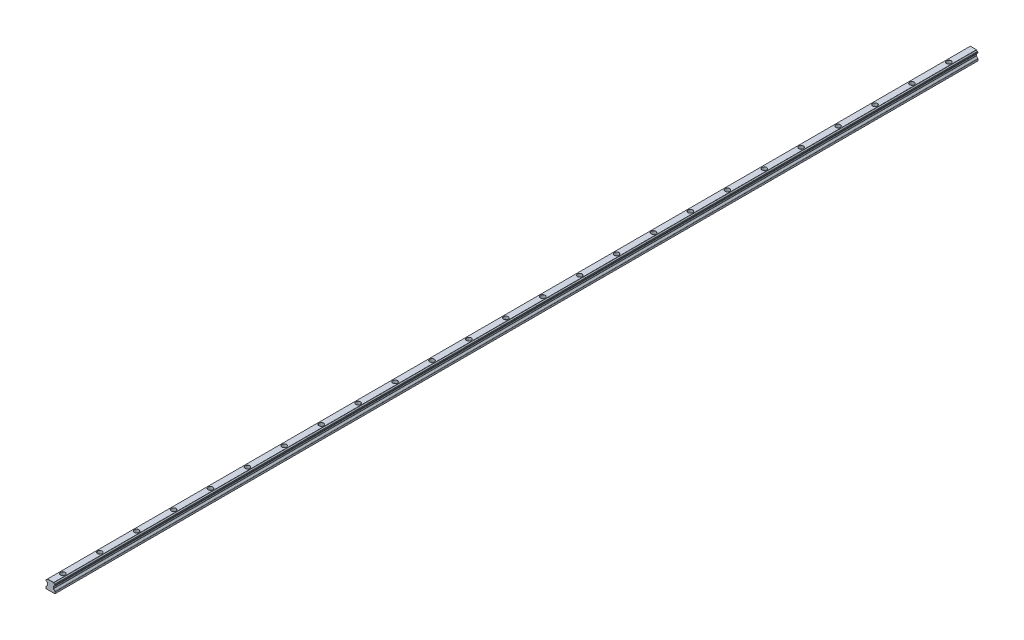
SolidWorks part; units mm, degrees
material "Plain Carbon Steel"
ref_plane "Front Plane" through (0, 0, 0) normal (0, 0, 1) x (1, 0, 0)
ref_plane "Top Plane" through (0, 0, 0) normal (0, 1, 0) x (1, 0, 0)
ref_plane "Right Plane" through (0, 0, 0) normal (1, 0, 0) x (0, 0, -1)
sketch "Rail Profile" plane through (0, 0, 0) normal (0, 0, 1) x (1, 0, 0)
  line L47 (0, 0) -> (0, 20) construction
  line L48 (-7, 0) -> (7, 0)
  line L49 (7, 0) -> (7.5, 0.5)
  line L50 (7.5, 0.5) -> (7.5, 3.0858)
  line L58 (7.2071, 3.7929) -> (4.8672, 6.1328)
  line L59 (4.75, 6.4157) -> (4.75, 8.5843)
  line L60 (4.8672, 8.8672) -> (5.063, 9.063)
  line L61 (7.5, 11.6657) -> (7.5, 12.3343)
  line L62 (-7, 0) -> (-7.5, 0.5)
  line L63 (5, 15) -> (-5, 15)
  line L64 (6.75, 9) -> (6.75, 15) construction
  line L65 (5.063, 14.937) -> (5, 15)
  line L66 (-7.5, 0.5) -> (-7.5, 3.0858)
  line L67 (6.75, 15) -> (3.75, 12) construction
  line L68 (3.75, 12) -> (6.75, 9) construction
  line L69 (7.1, 12.3343) -> (7.1, 11.6657) construction
  line L70 (6.4042, 13.0301) -> (6.4042, 10.9699) construction
  line L71 (-7.2071, 3.7929) -> (-4.8672, 6.1328)
  line L72 (-4.75, 6.4157) -> (-4.75, 8.5843)
  line L73 (-4.8672, 8.8672) -> (-5.063, 9.063)
  line L74 (5, 15) -> (8, 12) construction
  line L75 (4.8672, 8.8672) -> (8, 12) construction
  line L76 (-7.5, 11.6657) -> (-7.5, 12.3343)
  line L77 (-5.063, 14.937) -> (-5, 15)
  arc A4 (6.4734, 13.4241) -> (5.1741, 14.7234) centre (6.75, 15) cw
  arc A6 (5.1741, 9.2766) -> (6.4734, 10.5759) centre (6.75, 9) cw
  arc A7 (7.2071, 3.7929) -> (7.5, 3.0858) centre (6.5, 3.0858) cw
  arc A8 (5.063, 14.937) -> (5.1741, 14.7234) centre (4.7801, 14.6542) cw
  arc A9 (6.4734, 13.4241) -> (6.8012, 13.0792) centre (6.4042, 13.0301) cw
  arc A10 (7.1491, 12.7313) -> (7.5, 12.3343) centre (7.1, 12.3343) cw
  arc A11 (7.5, 11.6657) -> (7.1491, 11.2687) centre (7.1, 11.6657) cw
  arc A12 (6.8012, 10.9208) -> (6.4734, 10.5759) centre (6.4042, 10.9699) cw
  arc A13 (5.1741, 9.2766) -> (5.063, 9.063) centre (4.7801, 9.3458) cw
  arc A14 (4.8672, 8.8672) -> (4.75, 8.5843) centre (5.15, 8.5843) ccw
  arc A15 (4.75, 6.4157) -> (4.8672, 6.1328) centre (5.15, 6.4157) ccw
  arc A16 (6.8012, 13.0792) -> (7.1491, 12.7313) centre (7.1981, 13.1283) ccw
  arc A17 (7.1491, 11.2687) -> (6.8012, 10.9208) centre (7.1981, 10.8717) ccw
  arc A18 (-7.2071, 3.7929) -> (-7.5, 3.0858) centre (-6.5, 3.0858) ccw
  arc A19 (-4.75, 6.4157) -> (-4.8672, 6.1328) centre (-5.15, 6.4157) cw
  arc A20 (-4.8672, 8.8672) -> (-4.75, 8.5843) centre (-5.15, 8.5843) cw
  arc A21 (-5.1741, 9.2766) -> (-5.063, 9.063) centre (-4.7801, 9.3458) ccw
  arc A22 (-5.1741, 9.2766) -> (-6.4734, 10.5759) centre (-6.75, 9) ccw
  arc A23 (-6.8012, 10.9208) -> (-6.4734, 10.5759) centre (-6.4042, 10.9699) ccw
  arc A24 (-7.1491, 11.2687) -> (-6.8012, 10.9208) centre (-7.1981, 10.8717) cw
  arc A25 (-7.5, 11.6657) -> (-7.1491, 11.2687) centre (-7.1, 11.6657) ccw
  arc A26 (-7.1491, 12.7313) -> (-7.5, 12.3343) centre (-7.1, 12.3343) ccw
  arc A27 (-6.8012, 13.0792) -> (-7.1491, 12.7313) centre (-7.1981, 13.1283) cw
  arc A28 (-6.4734, 13.4241) -> (-6.8012, 13.0792) centre (-6.4042, 13.0301) ccw
  arc A29 (-6.4734, 13.4241) -> (-5.1741, 14.7234) centre (-6.75, 15) ccw
  arc A30 (-5.063, 14.937) -> (-5.1741, 14.7234) centre (-4.7801, 14.6542) ccw
  point P2 (4.75, 7.5)
  point P12 (7.5, 12)
  point P19 (6.75, 12)
  point P25 (5.1578, 14.8422)
  point P50 (8, 12)
  point P78 (0, 15)
  dimension "Rb" = 1.6
  dimension "Rf1" = 1
  dimension "Rf2" = 0.4
  dimension "WR" = 15
  dimension "Wi" = 9.5
  dimension "Wt" = 5
  dimension "Ac" = 135
  dimension "HR" = 15
  dimension "Hm" = 7.5
  dimension "Hb" = 12
  dimension "Hc" = 0.5
  dimension "Wb" = 7.5
extrude "Body" add sketch "Rail Profile" against normal blind 1500
chamfer "Aesthetic Chamfer" distance 0.15 angle 45 84 edges at (-5.0315, 14.9685, 0) (-5.135, 14.8388, 0) (-5.6186, 13.8686, 0) (-6.6941, 13.3057, 0) (-6.9153, 12.8454, 0) (-7.3997, 12.5992, 0) (-7.5, 12, 0) (-7.3997, 11.4008, 0) (-6.9153, 11.1546, 0) (-6.6941, 10.6943, 0) (-5.6186, 10.1314, 0) (-5.135, 9.1612, 0) (-4.9651, 8.9651, 0) (-4.7804, 8.7374, 0) (-4.75, 7.5, 0) (-4.7804, 6.2626, 0) (-6.0371, 4.9629, 0) (-7.4239, 3.4685, 0) (-7.5, 1.7929, 0) (-7.25, 0.25, 0) (0, 0, 0) (7.25, 0.25, 0) (5.0315, 14.9685, 0) (5.135, 14.8388, 0) (5.6186, 13.8686, 0) (6.6941, 13.3057, 0) (6.9153, 12.8454, 0) (7.3997, 12.5992, 0) (7.5, 12, 0) (7.3997, 11.4008, 0) (6.9153, 11.1546, 0) (6.6941, 10.6943, 0) (5.6186, 10.1314, 0) (5.135, 9.1612, 0) (4.9651, 8.9651, 0) (4.7804, 8.7374, 0) (7.5, 1.7929, 0) (4.75, 7.5, 0) (7.4239, 3.4685, 0) (4.7804, 6.2626, 0) (6.0371, 4.9629, 0) (0, 15, 0) (5.0315, 14.9685, -1500) (5.135, 14.8388, -1500) (5.6186, 13.8686, -1500) (6.6941, 13.3057, -1500) (6.9153, 12.8454, -1500) (7.3997, 12.5992, -1500) (7.5, 12, -1500) (7.3997, 11.4008, -1500) (6.9153, 11.1546, -1500) (6.6941, 10.6943, -1500) (5.6186, 10.1314, -1500) (5.135, 9.1612, -1500) (4.9651, 8.9651, -1500) (4.7804, 8.7374, -1500) (4.75, 7.5, -1500) (4.7804, 6.2626, -1500) (6.0371, 4.9629, -1500) (7.4239, 3.4685, -1500) (7.5, 1.7929, -1500) (7.25, 0.25, -1500) (0, 0, -1500) (-7.25, 0.25, -1500) (-5.0315, 14.9685, -1500) (-5.135, 14.8388, -1500) (-5.6186, 13.8686, -1500) (-6.6941, 13.3057, -1500) (-6.9153, 12.8454, -1500) (-7.3997, 12.5992, -1500) (-7.5, 12, -1500) (-7.3997, 11.4008, -1500) (-6.9153, 11.1546, -1500) (-6.6941, 10.6943, -1500) (-5.6186, 10.1314, -1500) (-7.5, 1.7929, -1500) (-5.135, 9.1612, -1500) (-7.4239, 3.4685, -1500) (-4.9651, 8.9651, -1500) (-6.0371, 4.9629, -1500) (-4.7804, 8.7374, -1500) (-4.7804, 6.2626, -1500) (-4.75, 7.5, -1500) (0, 15, -1500)
hole_wizard "Mounting Hole" positions "3DSketch1" profile "Sketch1" counterbore size "M4" standard "ISO" end condition through all
sketch3d "3DSketch1"
  point P0 (0, 15, -20)
  dimension "D1" = 7.5
  dimension "E1" = 20
sketch "Sketch1" plane through (0, 15, -20) normal (1, 0, 0) x (0, 0, 1)
  line L0 (0, 0) -> (0, 15)
  line L1 (2.25, 14.9) -> (2.35, 15)
  line L2 (2.25, 14.9) -> (2.25, 5.4)
  line L3 (2.25, 5.4) -> (2.35, 5.3)
  line L4 (2.35, 5.3) -> (3.75, 5.3)
  line L5 (3.75, 5.3) -> (3.75, 0.1)
  line L6 (3.75, 0.1) -> (3.85, 0)
  line L7 (3.85, 0) -> (0, 0)
  line L8 (-3.75, 0.1) -> (-3.85, 0) construction
  line L9 (-2.25, 5.4) -> (-2.35, 5.3) construction
  line L11 (0, -6.35) -> (0, 107.95) construction
  line L12 (2.35, 15) -> (0, 15)
  line L13 (-2.25, 14.9) -> (-2.35, 15) construction
  dimension "Thru Hole Dia." = 4.5
  dimension "Thru Hole Depth" = 15
  dimension "C'Bore Dia." = 7.5
  dimension "C'Bore Depth" = 5.3
  dimension "Near C'Sink Dia." = 7.7
  dimension "Near C'Sink Angle" = 90
  dimension "Mid C'Sink Dia." = 4.7
  dimension "Mid C'Sink Angle" = 90
  dimension "Far C'Sink Dia." = 4.7
  dimension "Far C'Sink Angle" = 90
fillet "Production Fillet" radius 0.1 1 edges at (0, 9.7, -16.25)
pattern_linear "Mounting Holes Pattern" count 25 spacing 60 along (0, 0, -1) of "Mounting Hole", "Production Fillet"
equation "\"Wt@Rail Profile\"= \"WR@Rail Profile\" / 3'Top Side Half Width"
equation "\"Hm@Rail Profile\"= \"HR@Rail Profile\" / 2'Recirculation Avoidance Height"
equation "\"Hb@Rail Profile\"= 0.8 * \"HR@Rail Profile\"'Pivot Height"
equation "\"Hc@Rail Profile\"= \"WR@Rail Profile\" / 30'Chamfer Width"
equation "\"Wb@Rail Profile\"= \"WR@Rail Profile\" / 2'Ball Center Cross Width"
equation "\"D1@3DSketch1\"= \"WR@Rail Profile\" / 2'Hole Center Position"
